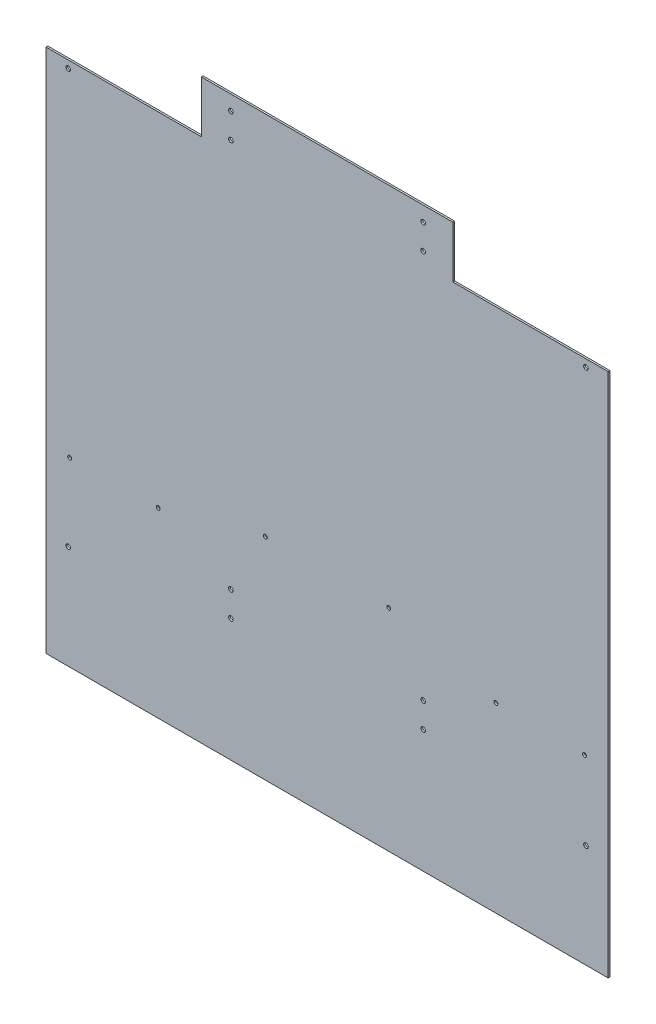
SolidWorks part; units mm, degrees
material "PC High Viscosity"
ref_plane "Front Plane" through (0, 0, 0) normal (0, 0, 1) x (1, 0, 0)
ref_plane "Top Plane" through (0, 0, 0) normal (0, 1, 0) x (1, 0, 0)
ref_plane "Right Plane" through (0, 0, 0) normal (1, 0, 0) x (0, 0, -1)
sketch "Sketch2" plane through (0, 0, 0) normal (0, 0, 1) x (1, 0, 0)
  line L0 (-482.6, 901.7) -> (-215.9, 901.7)
  line L1 (-482.6, 0) -> (482.6, 0)
  line L2 (-482.6, 0) -> (-482.6, 901.7)
  line L4 (482.6, 0) -> (482.6, 901.7)
  line L5 (-215.9, 901.7) -> (-215.9, 990.6)
  line L6 (-215.9, 990.6) -> (215.9, 990.6)
  line L7 (215.9, 990.6) -> (215.9, 901.7)
  line L8 (215.9, 901.7) -> (482.6, 901.7)
  line L9 (0, 0) -> (0, 990.6) construction
  dimension "D1" = 990.6
  dimension "D2" = 965.2
  dimension "D3" = 88.9
  dimension "D4" = 431.8
extrude "Boss-Extrude1" add sketch "Sketch2" along normal blind 3.175
hole_wizard "1/4 Clearance Hole1" positions "Sketch3" profile "Sketch4" hole size "1/4" standard "ANSI Inch" end condition through all
sketch "Sketch3" plane through (0, 0, 3.175) normal (0, 0, 1) x (1, 0, 0)
  line L0 (0, 0) -> (0, 990.6) construction
  line L1 (-482.6, 0) -> (482.6, 0) construction
  line L4 (-9.861, 373.4082) -> (0, 410.21) construction
  line L5 (-9.861, 373.4082) -> (472.739, 244.0959) construction
  line L6 (0, 410.21) -> (482.6, 280.8977) construction
  line L7 (472.739, 244.0959) -> (482.6, 280.8977) construction
  line L8 (482.6, 0) -> (482.6, 901.7) construction
  line L9 (12.7, 406.807) -> (2.839, 370.0053) construction
  line L11 (-4.9305, 391.8091) -> (477.6695, 262.4968) construction
  line L14 (0, 410.21) -> (1.6435, 416.3436) construction
  line L15 (0, 410.21) -> (480.9565, 281.3381) construction
  line L16 (1.6435, 416.3436) -> (482.6, 287.4717) construction
  line L17 (480.9565, 281.3381) -> (482.6, 287.4717) construction
  line L18 (215.9, 990.6) -> (-215.9, 990.6) construction
  circle A0 centre (441.96, 311.5092) radius 6.35 construction
  point P178 (105.9076, 362.1101)
  point P180 (289.9164, 312.8051)
  point P183 (-289.9164, 312.8051)
  point P184 (-105.9076, 362.1101)
  point P566 (441.96, 311.5092)
  point P569 (-441.96, 311.5092)
  dimension "D10" = 12.7
  dimension "D11" = 6.35
  dimension "D1" = 15
  dimension "D2" = 12.7
  dimension "D3" = 38.1
  dimension "D4" = 410.21
  dimension "D5" = 101.6
  dimension "D6" = 292.1
  dimension "D9" = 6.35
  dimension "D12" = 439.2982
  dimension "D7" = 441.96
sketch "Sketch4" plane through (-441.96, 311.5092, 3.175) normal (1, 0, 0) x (0, -1, 0)
  line L0 (0, 0) -> (0, 3.175)
  line L1 (0, 3.175) -> (3.3782, 3.175)
  line L2 (3.3782, 3.175) -> (3.3782, 0)
  line L5 (3.3782, 0) -> (0, 0)
  line L11 (0, -6.35) -> (0, 107.95) construction
  dimension "Thru Hole Dia." = 6.7564
  dimension "Thru Hole Depth" = 3.175
hole_wizard "5/16 (0.3125) Diameter Hole1" positions "Sketch5" profile "Sketch6" hole size "5/16" standard "ANSI Inch" end condition through all
sketch "Sketch5" plane through (0, 0, 3.175) normal (0, 0, 1) x (1, 0, 0)
  line L1 (-215.9, 962.66) -> (215.9, 962.66) construction
  line L2 (-215.9, 962.66) -> (-215.9, 924.56) construction
  line L3 (-215.9, 924.56) -> (215.9, 924.56) construction
  line L4 (215.9, 962.66) -> (215.9, 924.56) construction
  line L5 (-215.9, 990.6) -> (-215.9, 901.7) construction
  line L6 (215.9, 901.7) -> (215.9, 990.6) construction
  line L7 (0, 990.6) -> (0, 0) construction
  line L8 (215.9, 990.6) -> (-215.9, 990.6) construction
  line L9 (-482.6, 0) -> (482.6, 0) construction
  line L10 (165.1, 922.02) -> (165.1, 210.82) construction
  point P0 (-165.1, 922.02)
  point P2 (-165.1, 965.2)
  point P4 (165.1, 965.2)
  point P6 (165.1, 922.02)
  point P125 (-165.1, 210.82)
  point P126 (-165.1, 254)
  point P127 (165.1, 254)
  point P128 (165.1, 210.82)
  point P131 (-444.5, 177.8)
  point P137 (444.5, 177.8)
  point P150 (-444.5, 889)
  point P151 (444.5, 889)
  dimension "D1" = 38.1
  dimension "D2" = 2.54
  dimension "D3" = 2.54
  dimension "D4" = 924.56
  dimension "D5" = 50.8
  dimension "D7" = 711.2
  dimension "D8" = 177.8
  dimension "D11" = 711.2
  dimension "D9" = 444.5
  dimension "D6" = 2
  dimension "D10" = 2
sketch "Sketch6" plane through (-165.1, 922.02, 3.175) normal (1, 0, 0) x (0, -1, 0)
  line L0 (0, 0) -> (0, 3.175)
  line L1 (0, 3.175) -> (3.9688, 3.175)
  line L2 (3.9688, 3.175) -> (3.9688, 0)
  line L5 (3.9688, 0) -> (0, 0)
  line L11 (0, -6.35) -> (0, 107.95) construction
  dimension "Thru Hole Dia." = 7.9375
  dimension "Thru Hole Depth" = 3.175
equation "\"D3@Sketch5\"=\"D2@Sketch5\""
